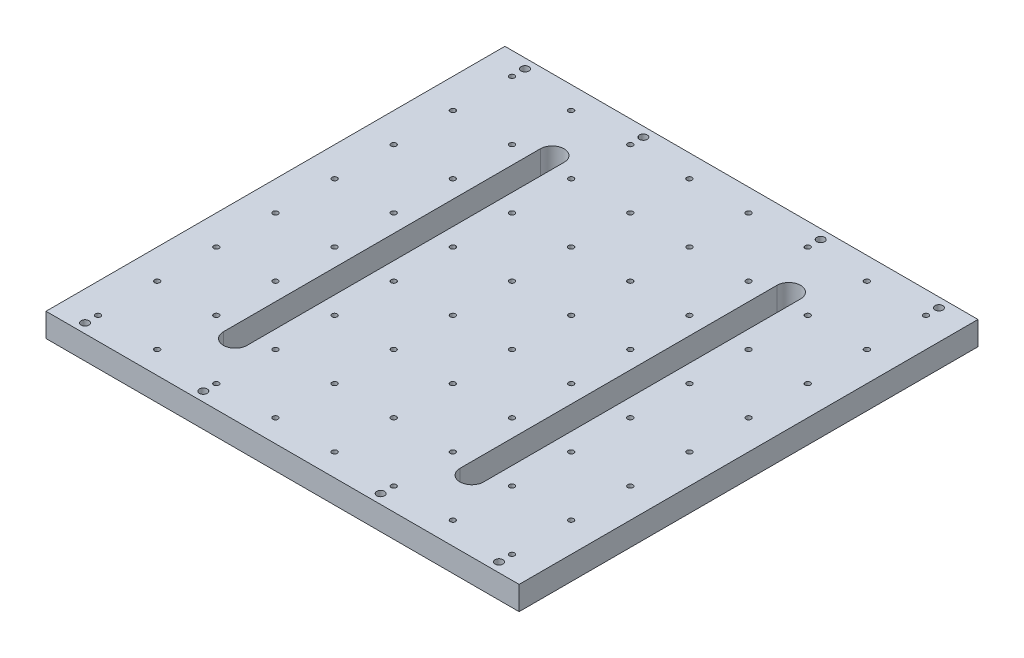
SolidWorks part; units mm, degrees
ref_plane "Front Plane" through (0, 0, 0) normal (0, 0, 1) x (1, 0, 0)
ref_plane "Top Plane" through (0, 0, 0) normal (0, 1, 0) x (1, 0, 0)
ref_plane "Right Plane" through (0, 0, 0) normal (1, 0, 0) x (0, 0, -1)
sketch "Sketch1" plane through (0, 0, 0) normal (0, 1, 0) x (1, 0, 0)
  line L1 (0, 0) -> (3, 0) construction
  line L2 (0, 0) -> (0, 200) construction
  line L3 (0, 200) -> (3, 200) construction
  line L4 (3, 3) -> (3, 197) construction
  line L5 (3, 200) -> (203, 200) construction
  line L7 (3, 197) -> (203, 197) construction
  line L9 (203, 200) -> (206, 200) construction
  line L10 (203, 197) -> (203, 3) construction
  line L11 (203, 0) -> (206, 0) construction
  line L12 (206, 200) -> (206, 0) construction
  line L13 (203, 0) -> (3, 0) construction
  line L15 (203, 3) -> (3, 3) construction
  line L17 (3, 197) -> (203, 197)
  line L18 (3, 197) -> (3, 3)
  line L19 (3, 3) -> (203, 3)
  line L20 (203, 197) -> (203, 3)
  dimension "D1" = 3
  dimension "D2" = 200
  dimension "D3" = 3
  dimension "D4" = 200
  dimension "D5" = 200
  dimension "D6" = 3
  dimension "D7" = 3
  dimension "D8" = 200
extrude "Boss-Extrude2" add sketch "Sketch1" along normal blind 10
sketch "Sketch2" plane through (0, 10, 0) normal (0, 1, 0) x (1, 0, 0)
  line L0 (103, 197) -> (103, 3) construction
  line L1 (203, 197) -> (3, 197) construction
  line L2 (3, 3) -> (203, 3) construction
  line L3 (103, 100) -> (203, 100) construction
  line L4 (203, 3) -> (203, 197) construction
  line L5 (103, 100) -> (3, 100) construction
  line L6 (3, 197) -> (3, 3) construction
  line L7 (114.4, 187.5) -> (115.5, 187.5) construction
  line L8 (115.5, 187.5) -> (116.6, 187.5) construction
  line L9 (140.5, 187.5) -> (141.6, 187.5) construction
  line L10 (165.5, 187.5) -> (166.6, 187.5) construction
  line L11 (139.4, 187.5) -> (140.5, 187.5) construction
  line L12 (164.4, 187.5) -> (165.5, 187.5) construction
  line L13 (189.4, 187.5) -> (190.5, 187.5) construction
  line L14 (189.4, 12.5) -> (190.5, 12.5) construction
  line L15 (164.4, 12.5) -> (165.5, 12.5) construction
  line L16 (139.4, 12.5) -> (140.5, 12.5) construction
  line L17 (165.5, 12.5) -> (166.6, 12.5) construction
  line L18 (140.5, 12.5) -> (141.6, 12.5) construction
  line L19 (115.5, 12.5) -> (116.6, 12.5) construction
  line L20 (114.4, 12.5) -> (115.5, 12.5) construction
  line L21 (91.6, 12.5) -> (90.5, 12.5) construction
  line L22 (90.5, 12.5) -> (89.4, 12.5) construction
  line L23 (65.5, 12.5) -> (64.4, 12.5) construction
  line L24 (40.5, 12.5) -> (39.4, 12.5) construction
  line L25 (66.6, 12.5) -> (65.5, 12.5) construction
  line L26 (41.6, 12.5) -> (40.5, 12.5) construction
  line L27 (16.6, 12.5) -> (15.5, 12.5) construction
  circle A0 centre (115.5, 187.5) radius 1.1
  circle A1 centre (140.5, 187.5) radius 1.1
  circle A2 centre (165.5, 187.5) radius 1.1
  circle A3 centre (190.5, 187.5) radius 1.1
  circle A4 centre (115.5, 162.5) radius 1.1
  circle A5 centre (140.5, 162.5) radius 1.1
  circle A6 centre (165.5, 162.5) radius 1.1
  circle A7 centre (190.5, 162.5) radius 1.1
  circle A8 centre (115.5, 137.5) radius 1.1
  circle A9 centre (140.5, 137.5) radius 1.1
  circle A10 centre (165.5, 137.5) radius 1.1
  circle A11 centre (190.5, 137.5) radius 1.1
  circle A12 centre (115.5, 112.5) radius 1.1
  circle A13 centre (140.5, 112.5) radius 1.1
  circle A14 centre (165.5, 112.5) radius 1.1
  circle A15 centre (190.5, 112.5) radius 1.1
  circle A16 centre (65.5, 112.5) radius 1.1
  circle A17 centre (90.5, 112.5) radius 1.1
  circle A18 centre (40.5, 112.5) radius 1.1
  circle A19 centre (15.5, 112.5) radius 1.1
  circle A20 centre (15.5, 137.5) radius 1.1
  circle A21 centre (40.5, 137.5) radius 1.1
  circle A22 centre (65.5, 137.5) radius 1.1
  circle A23 centre (90.5, 137.5) radius 1.1
  circle A24 centre (65.5, 162.5) radius 1.1
  circle A25 centre (90.5, 162.5) radius 1.1
  circle A26 centre (40.5, 162.5) radius 1.1
  circle A27 centre (15.5, 162.5) radius 1.1
  circle A28 centre (15.5, 187.5) radius 1.1
  circle A29 centre (40.5, 187.5) radius 1.1
  circle A30 centre (65.5, 187.5) radius 1.1
  circle A31 centre (90.5, 187.5) radius 1.1
  circle A32 centre (190.5, 87.5) radius 1.1
  circle A33 centre (165.5, 87.5) radius 1.1
  circle A34 centre (140.5, 87.5) radius 1.1
  circle A35 centre (115.5, 87.5) radius 1.1
  circle A36 centre (190.5, 62.5) radius 1.1
  circle A37 centre (165.5, 62.5) radius 1.1
  circle A38 centre (140.5, 62.5) radius 1.1
  circle A39 centre (115.5, 62.5) radius 1.1
  circle A40 centre (190.5, 37.5) radius 1.1
  circle A41 centre (165.5, 37.5) radius 1.1
  circle A42 centre (140.5, 37.5) radius 1.1
  circle A43 centre (115.5, 37.5) radius 1.1
  circle A44 centre (190.5, 12.5) radius 1.1
  circle A45 centre (165.5, 12.5) radius 1.1
  circle A46 centre (140.5, 12.5) radius 1.1
  circle A47 centre (115.5, 12.5) radius 1.1
  circle A48 centre (90.5, 12.5) radius 1.1
  circle A49 centre (65.5, 12.5) radius 1.1
  circle A50 centre (40.5, 12.5) radius 1.1
  circle A51 centre (15.5, 12.5) radius 1.1
  circle A52 centre (90.5, 37.5) radius 1.1
  circle A53 centre (65.5, 37.5) radius 1.1
  circle A54 centre (40.5, 37.5) radius 1.1
  circle A55 centre (15.5, 37.5) radius 1.1
  circle A56 centre (90.5, 62.5) radius 1.1
  circle A57 centre (65.5, 62.5) radius 1.1
  circle A58 centre (40.5, 62.5) radius 1.1
  circle A59 centre (15.5, 62.5) radius 1.1
  circle A60 centre (90.5, 87.5) radius 1.1
  circle A61 centre (65.5, 87.5) radius 1.1
  circle A62 centre (40.5, 87.5) radius 1.1
  circle A63 centre (15.5, 87.5) radius 1.1
  point P10 (103, 112.5)
  point P14 (103, 137.5)
  point P15 (103, 162.5)
  point P16 (103, 187.5)
  point P21 (115.5, 162.5)
  point P23 (140.5, 162.5)
  point P24 (165.5, 162.5)
  point P25 (190.5, 162.5)
  point P26 (115.5, 137.5)
  point P27 (140.5, 137.5)
  point P28 (165.5, 137.5)
  point P29 (190.5, 137.5)
  point P30 (115.5, 112.5)
  point P31 (140.5, 112.5)
  point P32 (165.5, 112.5)
  point P33 (190.5, 112.5)
  point P139 (190.5, 87.5)
  point P140 (165.5, 87.5)
  point P141 (140.5, 87.5)
  point P142 (115.5, 87.5)
  point P143 (190.5, 62.5)
  point P144 (165.5, 62.5)
  point P145 (140.5, 62.5)
  point P146 (115.5, 62.5)
  point P147 (190.5, 37.5)
  point P148 (165.5, 37.5)
  point P149 (140.5, 37.5)
  point P150 (115.5, 37.5)
  point P190 (90.5, 37.5)
  point P191 (65.5, 37.5)
  point P192 (40.5, 37.5)
  point P193 (15.5, 37.5)
  point P194 (90.5, 62.5)
  point P195 (65.5, 62.5)
  point P196 (40.5, 62.5)
  point P197 (15.5, 62.5)
  point P198 (90.5, 87.5)
  point P199 (65.5, 87.5)
  point P200 (40.5, 87.5)
  point P201 (15.5, 87.5)
  dimension "D12" = 2.2
  dimension "D13" = 2.2
  dimension "D14" = 2.2
  dimension "D15" = 2.2
  dimension "D16" = 2.2
  dimension "D17" = 2.2
  dimension "D18" = 2.2
  dimension "D19" = 2.2
  dimension "D20" = 2.2
  dimension "D21" = 2.2
  dimension "D22" = 2.2
  dimension "D23" = 2.2
  dimension "D24" = 2.2
  dimension "D25" = 2.2
  dimension "D26" = 2.2
  dimension "D27" = 2.2
  dimension "D1" = 12.5
  dimension "D2" = 25
  dimension "D3" = 25
  dimension "D4" = 25
  dimension "D5" = 9.5
  dimension "D6" = 25
  dimension "D7" = 25
  dimension "D8" = 25
  dimension "D9" = 12.5
  dimension "D10" = 12.5
  dimension "D11" = 12.5
  dimension "D28" = 12.5
  dimension "D29" = 12.5
  dimension "D30" = 9.5
extrude "Cut-Extrude1" cut sketch "Sketch2" against normal blind 5
sketch "Sketch5" plane through (0, 10, 0) normal (0, 1, 0) x (1, 0, 0)
  line L0 (3, 197) -> (3, 189) construction
  line L1 (3, 197) -> (3, 3) construction
  line L2 (3, 189) -> (203, 189) construction
  line L3 (203, 3) -> (203, 197) construction
  line L4 (203, 189) -> (203, 197) construction
  line L5 (203, 197) -> (3, 197) construction
  line L6 (15.5, 187.5) -> (15.5, 197) construction
  line L8 (65.5, 187.5) -> (65.5, 197) construction
  line L9 (90.5, 187.5) -> (90.5, 189) construction
  line L10 (115.5, 187.5) -> (115.5, 189) construction
  line L11 (140.5, 187.5) -> (140.5, 197) construction
  line L12 (165.5, 187.5) -> (165.5, 189) construction
  line L13 (190.5, 187.5) -> (190.5, 197) construction
  line L14 (15.5, 193) -> (190.5, 193) construction
  line L15 (3, 100) -> (3, 197) construction
  line L16 (3, 100) -> (203, 100) construction
  line L23 (15.5, 7) -> (190.5, 7) construction
  line L24 (190.5, 12.5) -> (190.5, 3) construction
  line L26 (140.5, 12.5) -> (140.5, 3) construction
  line L29 (65.5, 12.5) -> (65.5, 3) construction
  line L31 (15.5, 12.5) -> (15.5, 3) construction
  line L32 (203, 3) -> (15.5, 3) construction
  line L33 (203, 11) -> (203, 3) construction
  line L34 (3, 11) -> (203, 11) construction
  circle A0 centre (15.5, 193) radius 1.65
  circle A2 centre (65.5, 193) radius 1.65
  circle A5 centre (140.5, 193) radius 1.65
  circle A7 centre (190.5, 193) radius 1.65
  circle A8 centre (190.5, 7) radius 1.65
  circle A9 centre (140.5, 7) radius 1.65
  circle A10 centre (65.5, 7) radius 1.65
  circle A11 centre (15.5, 7) radius 1.65
  point P34 (15.5, 193)
  point P86 (15.5, 7)
  dimension "D3" = 3.3
  dimension "D4" = 3.3
  dimension "D5" = 3.3
  dimension "D6" = 3.3
  dimension "D7" = 3.3
  dimension "D8" = 3.3
  dimension "D9" = 3.3
  dimension "D10" = 3.3
  dimension "D1" = 8
  dimension "D2" = 4
  dimension "D11" = 8
  dimension "D12" = 12.5
  dimension "D13" = 50
extrude "Cut-Extrude3" cut sketch "Sketch5" against normal through all
sketch "Sketch6" plane through (0, 10, 0) normal (0, 1, 0) x (1, 0, 0)
  line L0 (103, 197) -> (103, 3) construction
  line L1 (203, 197) -> (3, 197) construction
  line L2 (3, 3) -> (203, 3) construction
  line L3 (3, 197) -> (103, 197) construction
  line L4 (53, 197) -> (53, 3) construction
  line L5 (53, 33) -> (53, 167) construction
  line L6 (48, 33) -> (48, 167)
  line L7 (58, 33) -> (58, 167)
  line L8 (153, 33) -> (153, 167) construction
  line L9 (158, 33) -> (158, 167)
  line L10 (148, 33) -> (148, 167)
  arc A0 (48, 33) -> (58, 33) centre (53, 33) ccw
  arc A1 (58, 167) -> (48, 167) centre (53, 167) ccw
  arc A2 (158, 33) -> (148, 33) centre (153, 33) cw
  arc A3 (148, 167) -> (158, 167) centre (153, 167) cw
  point P10 (53, 33)
  point P11 (53, 167)
  point P14 (53, 100)
  point P21 (153, 100)
  dimension "D1" = 30
  dimension "D2" = 30
extrude "Cut-Extrude4" cut sketch "Sketch6" against normal blind 10
